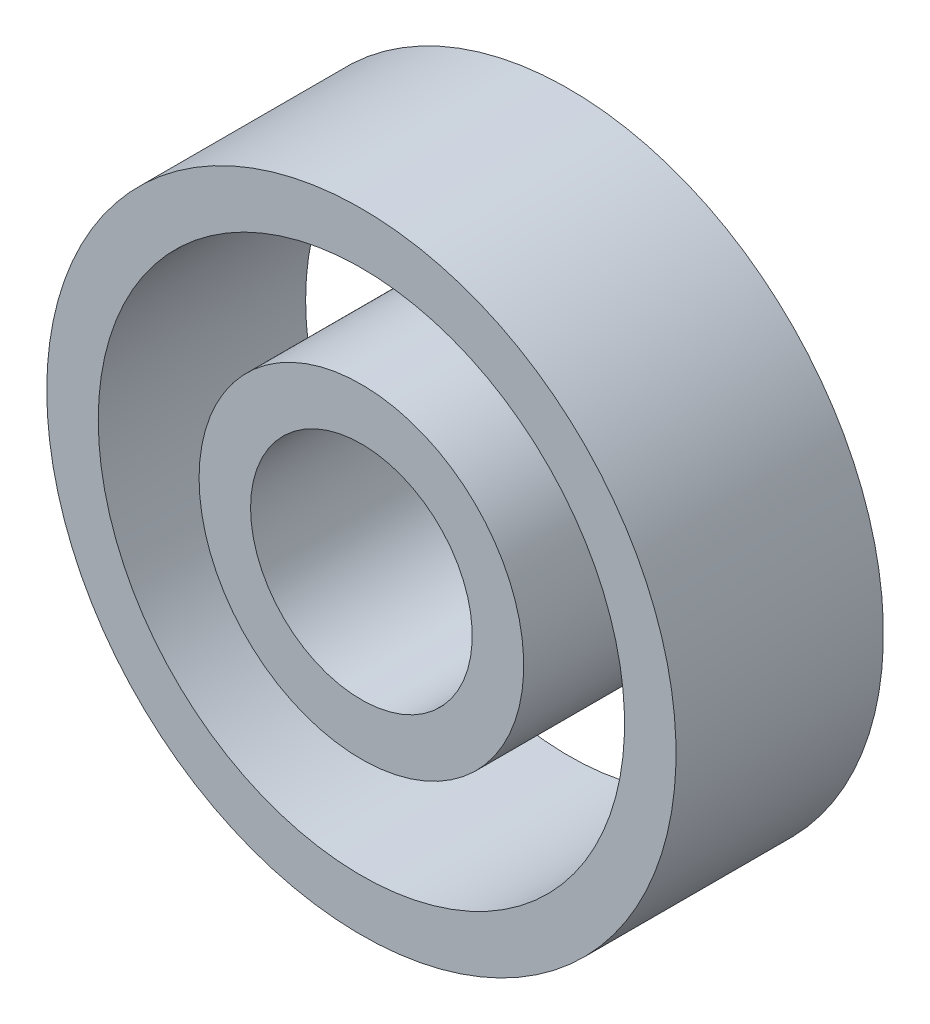
SolidWorks part; units mm, degrees
ref_plane "정면" through (0, 0, 0) normal (0, 0, 1) x (1, 0, 0)
ref_plane "윗면" through (0, 0, 0) normal (0, 1, 0) x (1, 0, 0)
ref_plane "우측면" through (0, 0, 0) normal (1, 0, 0) x (0, 0, -1)
sketch "스케치1" plane through (0, 0, 0) normal (0, 0, 1) x (1, 0, 0)
  circle A0 centre (0, 0) radius 11
  circle A1 centre (0, 0) radius 3.875
  circle A2 centre (0, 0) radius 5.675
  circle A3 centre (0, 0) radius 9.2
  dimension "D1" = 22
  dimension "D2" = 7.75
  dimension "D3" = 18.4
  dimension "D4" = 11.35
extrude "보스-돌출1" add sketch "스케치1" along normal blind 7.25 contours A0 A3 | A2 A1
